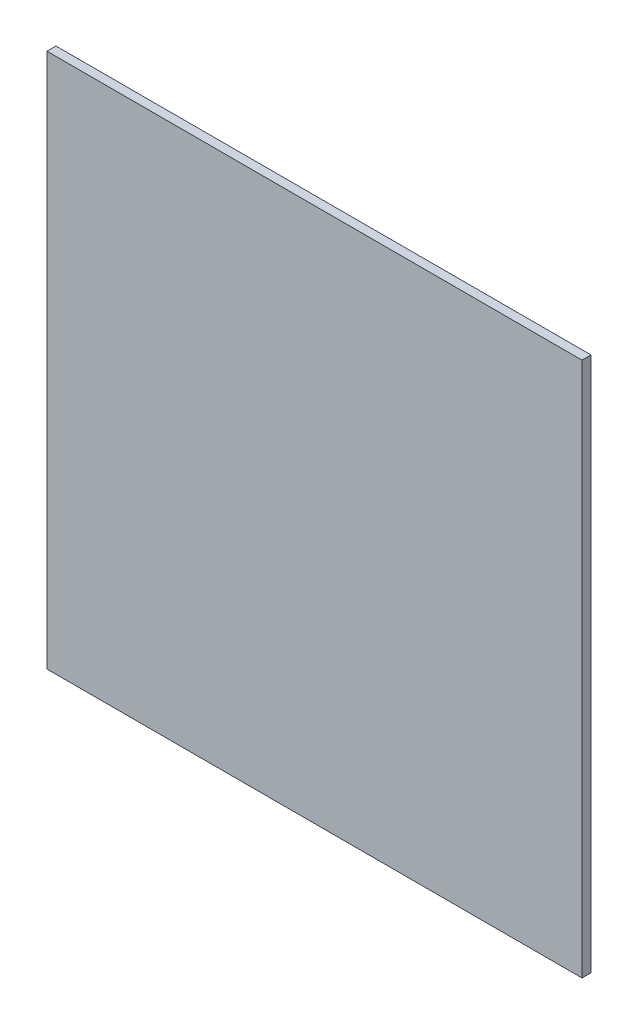
SolidWorks part; units mm, degrees
ref_plane "前视基准面" through (0, 0, 0) normal (0, 0, 1) x (1, 0, 0)
ref_plane "上视基准面" through (0, 0, 0) normal (0, 1, 0) x (1, 0, 0)
ref_plane "右视基准面" through (0, 0, 0) normal (1, 0, 0) x (0, 0, -1)
other "Configuration Table"
sketch "草图1" plane through (0, 0, 0) normal (0, 0, 1) x (1, 0, 0)
  line L1 (47.625, -47.625) -> (-47.625, -47.625)
  line L2 (47.625, -47.625) -> (47.625, 47.625)
  line L3 (47.625, 47.625) -> (-47.625, 47.625)
  line L4 (-47.625, -47.625) -> (-47.625, 47.625)
  line L5 (47.625, -47.625) -> (-47.625, 47.625) construction
  line L6 (47.625, 47.625) -> (-47.625, -47.625) construction
  point P0 (0, 0)
  dimension "D1" = 95.25
  dimension "D2" = 95.25
extrude "凸台-拉伸1" add sketch "草图1" along normal blind 1.6
